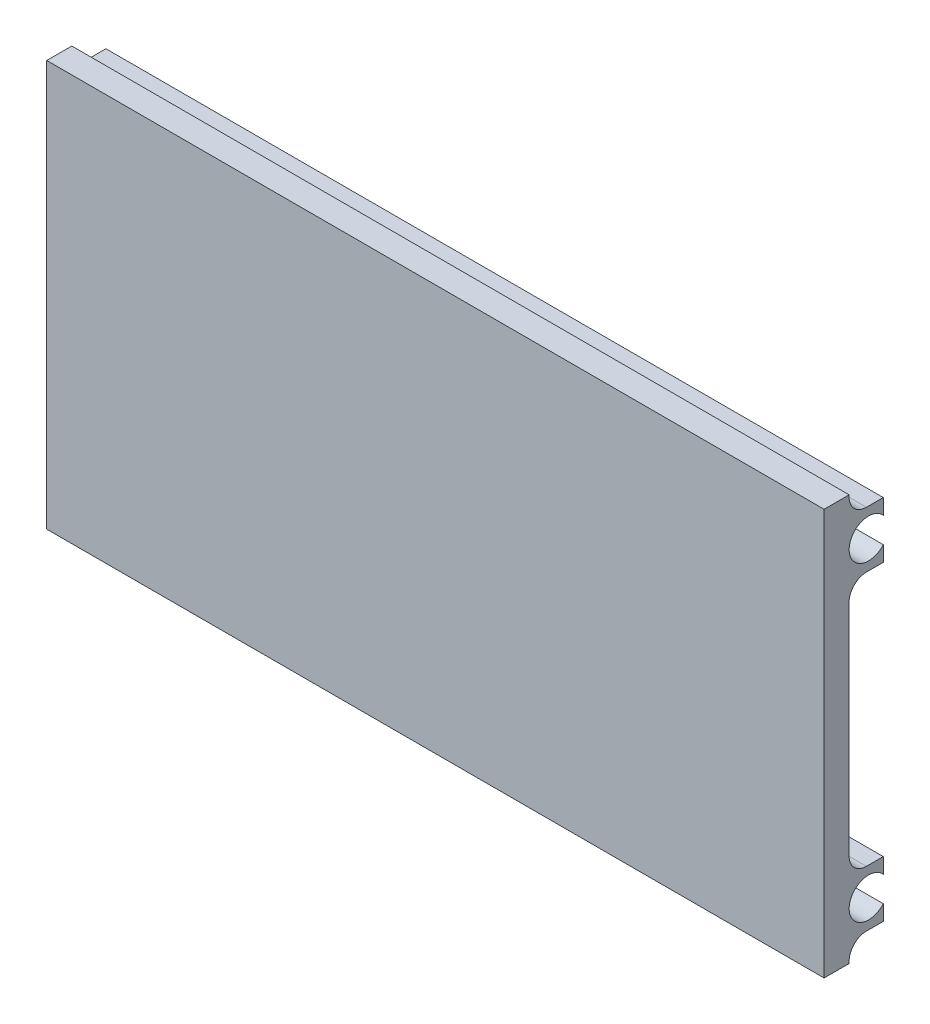
SolidWorks part; units mm, degrees
ref_plane "Спереди" through (0, 0, 0) normal (0, 0, 1) x (1, 0, 0)
ref_plane "Сверху" through (0, 0, 0) normal (0, 1, 0) x (1, 0, 0)
ref_plane "Справа" through (0, 0, 0) normal (1, 0, 0) x (0, 0, -1)
ref_plane "Плоскость4" through (90, 0, 0) normal (1, 0, 0) x (0, 0, -1)
sketch "Эскиз1" plane through (90, 0, 0) normal (1, 0, 0) x (0, 0, -1)
  line L0 (6.75, -24.0938) -> (6.75, 19.25)
  line L1 (6.75, 19.25) -> (-11.5938, 19.25)
  line L2 (-11.5938, 16.75) -> (-11, 16.75)
  line L3 (-11, 16.75) -> (-11, -16.75)
  line L4 (-11, -16.75) -> (-11.5938, -16.75)
  line L5 (-11.5938, -19.25) -> (-11, -19.25)
  line L6 (-11, -19.25) -> (-11, -23.5)
  line L7 (-11, -23.5) -> (-6.75, -23.5)
  line L8 (-6.75, -23.5) -> (-6.75, -24.0938)
  line L9 (-4.25, -24.0938) -> (-4.25, -23.5)
  line L10 (-4.25, -23.5) -> (4.25, -23.5)
  line L11 (4.25, -23.5) -> (4.25, -24.0938)
  arc A0 (-11.5938, 19.25) -> (-11.5938, 16.75) centre (-13.25, 18) ccw
  arc A1 (-11.5938, -16.75) -> (-11.5938, -19.25) centre (-13.25, -18) ccw
  arc A2 (-6.75, -24.0938) -> (-4.25, -24.0938) centre (-5.5, -25.75) ccw
  arc A3 (4.25, -24.0938) -> (6.75, -24.0938) centre (5.5, -25.75) ccw
extrude "Бобышка-Вытянуть1" add sketch "Эскиз1" against normal blind 90
sketch "Эскиз2" plane through (0, 19.25, 0) normal (0, 1, 0) x (-1, 0, 0)
  line L0 (-90, -6.75) -> (-90, 11)
  line L1 (-90, 11) -> (0, 11)
  line L2 (0, 11) -> (0, -6.75)
  line L3 (0, -6.75) -> (-90, -6.75)
extrude "Бобышка-Вытянуть2" add sketch "Эскиз2" along normal blind 8.2
sketch "Эскиз3" plane through (0, 0, -6.75) normal (0, 0, -1) x (-1, 0, 0)
  line L0 (0, -23.5) -> (-90, -23.5)
  line L1 (-90, -23.5) -> (-90, 27.45)
  line L2 (-90, 27.45) -> (0, 27.45)
  line L3 (0, 27.45) -> (0, -23.5)
extrude "Бобышка-Вытянуть3" add sketch "Эскиз3" along normal blind 8.2
sketch "Эскиз4" plane through (0, 0, 0) normal (-1, 0, 0) x (0, 0, 1)
  line L0 (-14.95, -14.75) -> (-11, -14.75)
  line L1 (-11, -14.75) -> (-11, 14.75)
  line L2 (-11, 14.75) -> (-14.95, 14.75)
  line L3 (-14.95, 14.75) -> (-14.95, -14.75)
extrude "Вырез-Вытянуть1" cut sketch "Эскиз4" against normal through all
sketch "Эскиз5" plane through (0, 0, 0) normal (-1, 0, 0) x (0, 0, 1)
  line L0 (-14.95, 27.45) -> (-14.95, 21.25)
  line L1 (-14.95, 21.25) -> (-11, 21.25)
  line L2 (-11, 21.25) -> (-11, 27.45)
  line L3 (-11, 27.45) -> (-14.95, 27.45)
extrude "Вырез-Вытянуть2" cut sketch "Эскиз5" against normal through all
sketch "Эскиз6" plane through (0, 0, 0) normal (-1, 0, 0) x (0, 0, 1)
  line L0 (-11, 27.45) -> (-11, 23.5)
  line L1 (-11, 23.5) -> (-8.75, 23.5)
  line L2 (-8.75, 23.5) -> (-8.75, 27.45)
  line L3 (-8.75, 27.45) -> (-11, 27.45)
extrude "Вырез-Вытянуть3" cut sketch "Эскиз6" against normal through all
sketch "Эскиз7" plane through (0, 0, 0) normal (-1, 0, 0) x (0, 0, 1)
  line L0 (-2.25, 27.45) -> (-2.25, 23.5)
  line L1 (-2.25, 23.5) -> (2.25, 23.5)
  line L2 (2.25, 23.5) -> (2.25, 27.45)
  line L3 (2.25, 27.45) -> (-2.25, 27.45)
extrude "Вырез-Вытянуть4" cut sketch "Эскиз7" against normal through all
sketch "Эскиз8" plane through (0, 0, 0) normal (-1, 0, 0) x (0, 0, 1)
  line L0 (11, 27.45) -> (8.75, 27.45)
  line L1 (8.75, 27.45) -> (8.75, 23.5)
  line L2 (8.75, 23.5) -> (11, 23.5)
  line L3 (11, 23.5) -> (11, 27.45)
extrude "Вырез-Вытянуть5" cut sketch "Эскиз8" against normal through all
sketch "Эскиз9" plane through (0, 0, 0) normal (-1, 0, 0) x (0, 0, 1)
  line L0 (-14.95, -23.5) -> (-11, -23.5)
  line L1 (-11, -23.5) -> (-11, -21.25)
  line L2 (-11, -21.25) -> (-14.95, -21.25)
  line L3 (-14.95, -21.25) -> (-14.95, -23.5)
extrude "Вырез-Вытянуть6" cut sketch "Эскиз9" against normal through all
sketch "Эскиз10" plane through (90, 0, 0) normal (1, 0, 0) x (0, 0, -1)
  line L0 (10.1, 22.6) -> (-10.1, 22.6)
  line L1 (-10.1, 22.6) -> (-10.1, -22.6)
  line L2 (-10.1, -22.6) -> (10.1, -22.6)
  line L3 (10.1, -22.6) -> (10.1, 22.6)
extrude "Вырез-Вытянуть7" cut sketch "Эскиз10" against normal blind 86
hole_wizard "Диаметр отверстия Ø2.5 (2.5)1" positions "Эскиз12" profile "Эскиз11" hole size "Ø2.5" standard "Ansi Metric"
sketch "Эскиз12" plane through (90, 0, 0) normal (1, 0, 0) x (0, 0, -1)
  point P0 (5.5, -25.75)
  point P1 (-13.25, -18)
  point P2 (-5.5, -25.75)
  point P3 (-13.25, 18)
sketch "Эскиз11" plane through (90, -25.75, -5.5) normal (0, 1, 0) x (0, 0, -1)
  line L0 (0, 0) -> (0, 90)
  line L1 (0, 90) -> (1.25, 90)
  line L2 (1.25, 90) -> (1.25, 0)
  line L5 (1.25, 0) -> (0, 0)
  line L11 (0, -6.35) -> (0, 107.95) construction
  dimension "Диаметр сквозного отверстия" = 2.5
  dimension "Глубина сквозного отверстия" = 90
hole_wizard "Диаметр отверстия Ø4.5 (4.5)1" positions "Эскиз14" profile "Эскиз13" hole size "Ø4.5" standard "Ansi Metric"
sketch "Эскиз14" plane through (0, 0, 0) normal (-1, 0, 0) x (0, 0, 1)
  point P0 (-13.25, -18)
  point P1 (-13.25, 18)
  point P2 (-5.5, 25.75)
  point P3 (5.5, 25.75)
sketch "Эскиз13" plane through (0, -18, -13.25) normal (0, 1, 0) x (0, 0, 1)
  line L0 (0, 0) -> (0, 90)
  line L1 (0, 90) -> (2.25, 90)
  line L2 (2.25, 90) -> (2.25, 0)
  line L5 (2.25, 0) -> (0, 0)
  line L11 (0, -6.35) -> (0, 107.95) construction
  dimension "Диаметр сквозного отверстия" = 4.5
  dimension "Глубина сквозного отверстия" = 90
hole_wizard "Диаметр отверстия Ø8.3 (8.3)1" positions "Эскиз16" profile "Эскиз15" hole size "Ø8.3" standard "Ansi Metric"
sketch "Эскиз16" plane through (0, 0, 0) normal (-1, 0, 0) x (0, 0, 1)
  point P0 (0, 0)
sketch "Эскиз15" plane through (0, 0, 0) normal (0, 1, 0) x (0, 0, 1)
  line L0 (0, 0) -> (0, 3.2)
  line L1 (0, 3.2) -> (4.15, 3.2)
  line L2 (4.15, 3.2) -> (4.15, 0)
  line L5 (4.15, 0) -> (0, 0)
  line L10 (0, 3.2) -> (-4.15, 3.2) construction
  line L11 (0, -6.35) -> (0, 107.95) construction
  dimension "Диаметр отверстия" = 8.3
  dimension "Глубина отверстия" = 3.2
  dimension "Угол заточки сверла" = 180
fillet "Скругление1" radius 2 1 edges at (45, 23.5, 8.75)
fillet "Скругление2" radius 2 11 edges at (4, -22.6, 0) (4, 0, -10.1) (4, 0, 10.1) (4, 22.6, 0) (45, -21.25, -11) (45, -14.75, -11) (45, 14.75, -11) (45, 21.25, -11) (45, 23.5, -8.75) (45, 23.5, -2.25) (45, 23.5, 2.25)
sketch "Эскиз17" plane through (90, 0, 0) normal (1, 0, 0) x (0, 0, -1)
  circle A0 centre (5.5, -25.75) radius 1.25 construction
  circle A1 centre (-5.5, -25.75) radius 1.25 construction
  circle A2 centre (-13.25, -18) radius 1.25 construction
  circle A3 centre (-13.25, 18) radius 1.25 construction
  circle A4 centre (5.5, -25.75) radius 1.25
  circle A5 centre (-5.5, -25.75) radius 1.25
  circle A6 centre (-13.25, -18) radius 1.25
  circle A7 centre (-13.25, 18) radius 1.25
extrude "Бобышка-Вытянуть4" add sketch "Эскиз17" against normal blind 90
sketch "Эскиз18" plane through (0, 0, 0) normal (-1, 0, 0) x (0, 0, 1)
  circle A0 centre (0, 0) radius 4.15 construction
  circle A1 centre (0, 0) radius 4.15
extrude "Вырез-Вытянуть8" cut sketch "Эскиз18" against normal blind 100
sketch "Эскиз19" plane through (90, 0, 0) normal (1, 0, 0) x (0, 0, -1)
  line L0 (10.1, -22.6) -> (10.1, 22.6) construction
  line L1 (10.1, -22.6) -> (10.1, 22.6)
  line L2 (10.1, 22.6) -> (10.1, 31.0193)
  line L3 (10.1, 31.0193) -> (-21.7226, 31.0193)
  line L4 (-21.7226, 31.0193) -> (-21.7226, -29.7455)
  line L5 (-21.7226, -29.7455) -> (10.1, -29.7455)
  line L6 (10.1, -29.7455) -> (10.1, -22.6)
extrude "Вырез-Вытянуть9" cut sketch "Эскиз19" against normal blind 110
sketch "Эскиз20" plane through (90, 0, 0) normal (1, 0, 0) x (0, 0, -1)
  line L0 (10.1, -23.5) -> (10.1, 23.6086) construction
  line L1 (10.1, 23.5) -> (10.1, 23.6086)
  line L2 (10.75, 23.5) -> (10.1, 23.5)
  arc A0 (10.1, 23.6086) -> (10.75, 23.5) centre (10.75, 25.5) ccw construction
  arc A1 (10.1, 23.6086) -> (10.75, 23.5) centre (10.75, 25.5) ccw
extrude "Вырез-Вытянуть10" cut sketch "Эскиз20" against normal blind 110
sketch "Эскиз21" plane through (0, 0, -10.1) normal (0, 0, 1) x (1, 0, 0)
  line L4 (90, -23.5) -> (90, 23.5)
  line L5 (90, 23.5) -> (0, 23.5)
  line L6 (0, 23.5) -> (0, -23.5)
  line L7 (0, -23.5) -> (90, -23.5)
  line L8 (90, -23.5) -> (90, 23.5)
  line L9 (90, 23.5) -> (0, 23.5)
  line L10 (0, 23.5) -> (0, -23.5)
  line L11 (0, -23.5) -> (90, -23.5)
  dimension "D1" = 0
extrude "Бобышка-Вытянуть5" add sketch "Эскиз21" along normal blind 2
